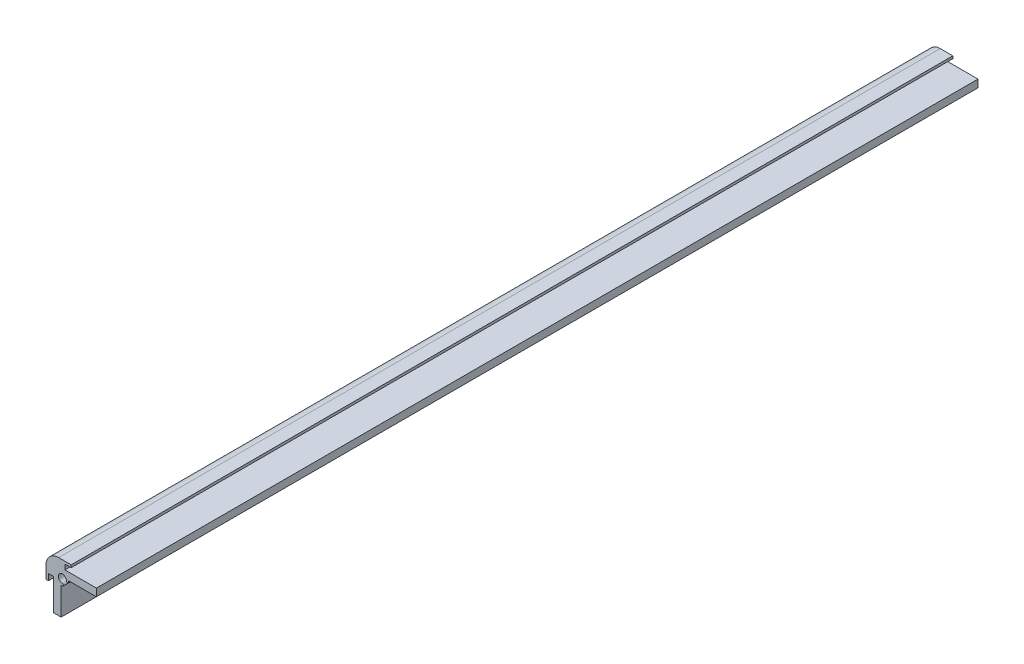
SolidWorks part; units mm, degrees
ref_plane "前视基准面" through (0, 0, 0) normal (0, 0, 1) x (1, 0, 0)
ref_plane "上视基准面" through (0, 0, 0) normal (0, 1, 0) x (1, 0, 0)
ref_plane "右视基准面" through (0, 0, 0) normal (1, 0, 0) x (0, 0, -1)
sketch "Model" plane through (0, 0, 0) normal (0, 0, 1) x (1, 0, 0)
  line L0 (1340.1386, 805.8626) -> (1345.1386, 805.8626)
  line L1 (1335.1386, 800.8626) -> (1335.1386, 795.8626)
  line L2 (1335.1386, 795.8626) -> (1336.1386, 795.8626)
  line L3 (1336.1386, 798.3626) -> (1338.1386, 798.3626)
  line L4 (1338.1386, 798.3626) -> (1338.1386, 785.8626)
  line L5 (1338.1386, 785.8626) -> (1341.1386, 785.8626)
  line L6 (1345.1386, 805.8626) -> (1345.1386, 804.8626)
  line L7 (1342.6386, 804.8626) -> (1342.6386, 802.8626)
  line L8 (1342.6386, 802.8626) -> (1355.1386, 802.8626)
  line L9 (1355.1386, 802.8626) -> (1355.1386, 799.8626)
  line L10 (1355.1386, 799.8626) -> (1344.0386, 799.8626)
  line L11 (1341.1386, 785.8626) -> (1341.1386, 796.8626)
  line L12 (1341.1386, 796.8626) -> (1341.4833, 796.8626)
  line L13 (1344.0386, 799.3626) -> (1344.0386, 799.8626)
  line L14 (1336.1386, 795.8626) -> (1336.1386, 798.3626)
  line L15 (1345.1386, 804.8626) -> (1342.6386, 804.8626)
  arc A0 (1340.1386, 805.8626) -> (1335.1386, 800.8626) centre (1340.1386, 800.8626) ccw
  arc A1 (1343.2386, 799.3626) -> (1341.6386, 797.7626) centre (1341.6386, 799.3626) ccw
  arc A2 (1343.2386, 799.3626) -> (1344.0386, 799.3626) centre (1343.6386, 799.3626) ccw
  arc A3 (1341.4833, 796.8626) -> (1341.6386, 797.7626) centre (1341.6386, 797.2992) ccw
extrude "凸台-拉伸1" add sketch "Model" along normal blind 350
